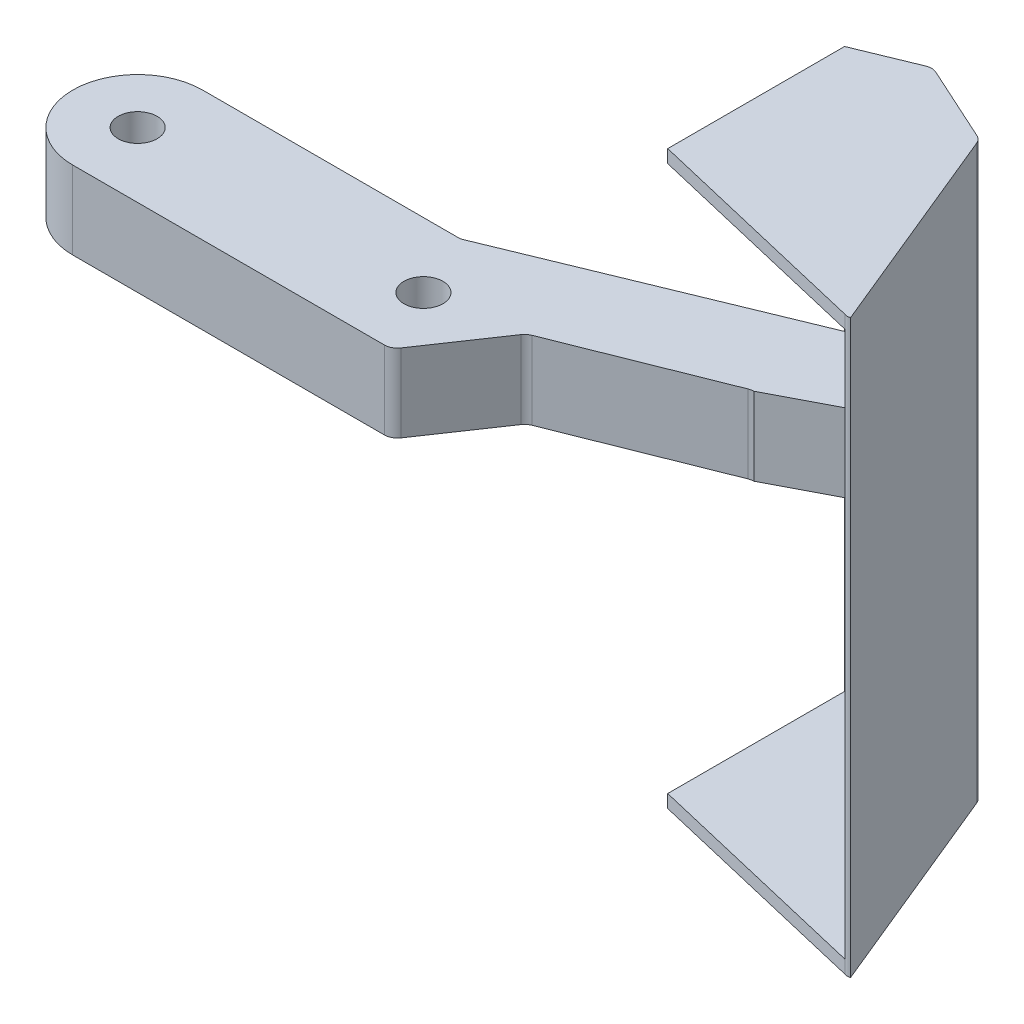
SolidWorks part; units mm, degrees
ref_plane "Front Plane" through (0, 0, 0) normal (0, 0, 1) x (1, 0, 0)
ref_plane "Top Plane" through (0, 0, 0) normal (0, 1, 0) x (1, 0, 0)
ref_plane "Right Plane" through (0, 0, 0) normal (1, 0, 0) x (0, 0, -1)
sketch "Sketch1" plane through (0, 0, 0) normal (0, 1, 0) x (1, 0, 0)
  line L1 (0, -5) -> (23.9989, -5)
  line L2 (0, 5) -> (19.6524, 5)
  line L3 (20.0327, 5.0751) -> (45.2294, 15.4347)
  line L4 (46.0242, 15.4199) -> (51.8314, 12.7746)
  line L5 (52.3417, 12.2448) -> (55.4426, 4.7029)
  line L6 (24.8266, -4.5611) -> (28.5649, 0.9541)
  line L7 (29.0223, 1.322) -> (40.9296, 6.07)
  line L8 (41.6788, 6.0666) -> (47.1446, 3.8294)
  line L11 (47.1446, 3.8294) -> (48.0617, 3.087)
  line L12 (48.0617, 3.087) -> (48.8042, 4.0041)
  line L13 (48.8042, 4.0041) -> (49.7213, 3.2617)
  line L14 (49.7213, 3.2617) -> (50.4638, 4.1788)
  line L15 (50.4638, 4.1788) -> (51.3809, 3.4364)
  line L16 (51.3809, 3.4364) -> (52.1234, 4.3535)
  line L17 (52.1234, 4.3535) -> (53.0405, 3.6111)
  line L18 (53.0405, 3.6111) -> (53.783, 4.5282)
  line L19 (53.783, 4.5282) -> (54.7001, 3.7858)
  line L20 (54.7001, 3.7858) -> (55.4426, 4.7029)
  circle A0 centre (0, 0) radius 1.5
  arc A1 (0, 5) -> (0, -5) centre (0, 0) ccw
  circle A2 centre (22, 0) radius 1.5
  arc A3 (28.5649, 0.9541) -> (29.0223, 1.322) centre (29.3927, 0.3931) cw
  arc A4 (40.9296, 6.07) -> (41.6788, 6.0666) centre (41.2999, 5.1412) cw
  arc A5 (51.8314, 12.7746) -> (52.3417, 12.2448) centre (51.4169, 11.8646) cw
  arc A6 (45.2294, 15.4347) -> (46.0242, 15.4199) centre (45.6096, 14.5098) cw
  arc A7 (19.6524, 5) -> (20.0327, 5.0751) centre (19.6524, 6) ccw
  arc A8 (23.9989, -5) -> (24.8266, -4.5611) centre (23.9989, -4) ccw
  point P27 (28.7372, 1.2083)
  point P30 (41.3048, 6.2197)
  point P33 (52.1913, 12.6106)
  point P36 (45.63, 15.5994)
  point P39 (19.85, 5)
  point P42 (24.5291, -5)
  dimension "D1" = 3
  dimension "D2" = 10
  dimension "D4" = 3
  dimension "D20" = 1
  dimension "D3" = 22
  dimension "D5" = 124.13
  dimension "D6" = 7.5
  dimension "D7" = 214.13
  dimension "D8" = 13.53
  dimension "D9" = 224
  dimension "D10" = 6.31
  dimension "D11" = 157.65
  dimension "D12" = 19.85
  dimension "D13" = 25.78
  dimension "D14" = 7.21
  dimension "D15" = 133.16
  dimension "D16" = 136.84
  dimension "D17" = 8.55
  dimension "D18" = 1.18
  dimension "D19" = 1.18
extrude "Boss-Extrude1" add sketch "Sketch1" along normal blind 6
sketch "Croquis4" plane through (0, 0, 0) normal (0, -1, 0) x (1, 0, 0)
  line L1 (55.4426, -4.7029) -> (52.3417, -12.2448) construction
  line L5 (54.3012, -7.479) -> (54.1616, -7.8185)
  line L6 (51.8314, -12.7746) -> (46.0242, -15.4199)
  line L7 (45.2294, -15.4347) -> (40.6206, -13.5398)
  line L8 (45.2294, -15.4347) -> (20.0327, -5.0751) construction
  line L9 (58.701, 4.2285) -> (50.2217, -10.7882)
  line L10 (50.2217, -10.7882) -> (40.8065, -13.6162)
  line L11 (54.1616, -7.8185) -> (54.3012, -7.479)
  line L12 (52.3417, -12.2448) -> (58.8002, 3.4635)
  line L13 (58.8002, 3.4635) -> (59.1148, 4.2285)
  arc A1 (52.3417, -12.2448) -> (51.8314, -12.7746) centre (51.4169, -11.8646) cw
  arc A2 (46.0242, -15.4199) -> (45.2294, -15.4347) centre (45.6096, -14.5098) cw
  arc A3 (59.1148, 4.2285) -> (58.701, 4.2285) centre (58.9079, 3.7253) ccw
  arc M10 (45.2294, -15.4347) -> (46.0242, -15.4199) centre (45.6096, -14.5098) ccw
  line M11 (46.0242, -15.4199) -> (51.8314, -12.7746)
  arc M12 (51.8314, -12.7746) -> (52.3417, -12.2448) centre (51.4169, -11.8646) ccw
  line M13 (52.3417, -12.2448) -> (55.4426, -4.7029)
  line M14 (55.4426, -4.7029) -> (54.7001, -3.7858)
  line M15 (54.7001, -3.7858) -> (53.783, -4.5282)
  line M16 (53.783, -4.5282) -> (53.0405, -3.6111)
extrude "Saliente-Extruir7" add sketch "Croquis4" against normal blind 25 and the other way blind 19 contours L13 A3 L9 L12 M16 M15 M14 | L9 L10 L7 M10 M11 M12 M13 M14 M15 M16
sketch "Croquis5" plane through (0, 0, 0) normal (0, -1, 0) x (1, 0, 0)
  line L0 (41.3045, -6.1412) -> (50.2217, -10.7882)
  line L1 (41.3045, -6.1412) -> (47.1446, -3.8294)
  line L2 (47.1446, -3.8294) -> (48.0617, -3.087)
  line L3 (48.0617, -3.087) -> (48.8042, -4.0041)
  line L4 (48.8042, -4.0041) -> (49.7213, -3.2617)
  line L5 (49.7213, -3.2617) -> (50.4638, -4.1788)
  line L6 (50.4638, -4.1788) -> (51.3809, -3.4364)
  line L7 (51.3809, -3.4364) -> (52.1234, -4.3535)
  line L8 (52.1234, -4.3535) -> (53.0405, -3.6111)
  line L9 (53.0405, -3.6111) -> (53.601, -4.3035)
  line L11 (53.601, -4.3035) -> (53.7673, -4.5089)
  line L12 (53.7673, -4.5089) -> (50.2217, -10.7882)
  arc A0 (40.9296, -6.07) -> (41.6788, -6.0666) centre (41.2999, -5.1412) ccw construction
extrude "Cortar-Extruir2" cut sketch "Croquis5" against normal blind 25
ref_plane "Plano3" through (0, -19, 0) normal (0, -1, 0) x (-1, 0, 0)
sketch "Croquis6" plane through (0, -19, 0) normal (0, -1, 0) x (-1, 0, 0)
  line L0 (-40.8065, 13.6162) -> (-40.8065, 0)
  line L1 (-40.8065, 0) -> (-58.701, -4.2285)
  line L2 (-58.701, -4.2285) -> (-50.2217, 10.7882)
  line L3 (-50.2217, 10.7882) -> (-40.8065, 13.6162)
extrude "Saliente-Extruir8" add sketch "Croquis6" against normal blind 1
ref_plane "Plano4" through (0, 25, 0) normal (0, 1, 0) x (1, 0, 0)
sketch "Croquis7" plane through (0, 25, 0) normal (0, 1, 0) x (1, 0, 0)
  line L0 (40.8065, 0) -> (40.8065, 13.6162)
  line L1 (40.8065, 13.6162) -> (50.2217, 10.7882)
  line L2 (50.2217, 10.7882) -> (58.701, -4.2285)
  line L3 (58.701, -4.2285) -> (40.8065, 0)
extrude "Saliente-Extruir10" add sketch "Croquis7" against normal blind 1
